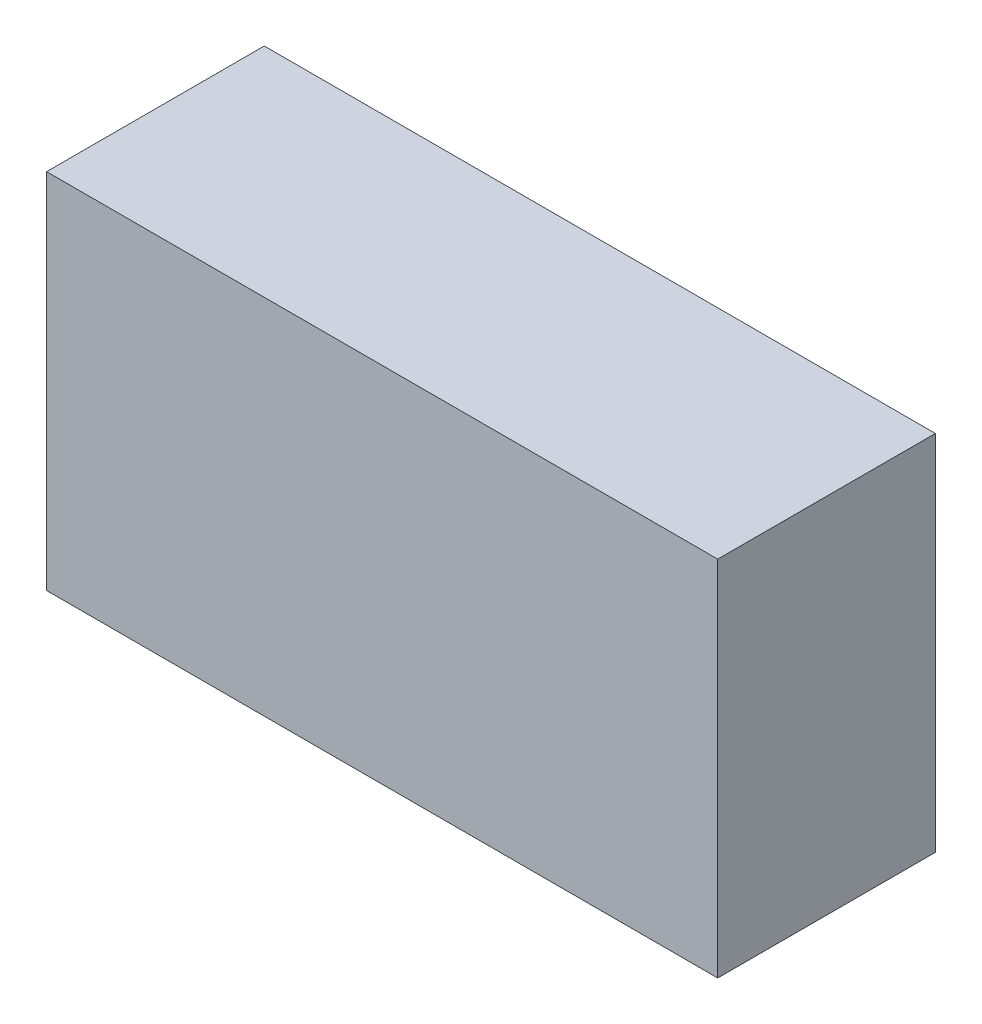
SolidWorks part; units mm, degrees
ref_plane "Front Plane" through (0, 0, 0) normal (0, 0, 1) x (1, 0, 0)
ref_plane "Top Plane" through (0, 0, 0) normal (0, 1, 0) x (1, 0, 0)
ref_plane "Right Plane" through (0, 0, 0) normal (1, 0, 0) x (0, 0, -1)
sketch "Sketch1" plane through (0, 0, 0) normal (0, 0, 1) x (1, 0, 0)
  line L1 (0, 0) -> (37, 0)
  line L2 (0, 0) -> (0, 20)
  line L3 (0, 20) -> (37, 20)
  line L4 (37, 0) -> (37, 20)
  dimension "D1" = 37
  dimension "D2" = 20
extrude "Boss-Extrude1" add sketch "Sketch1" along normal blind 12
